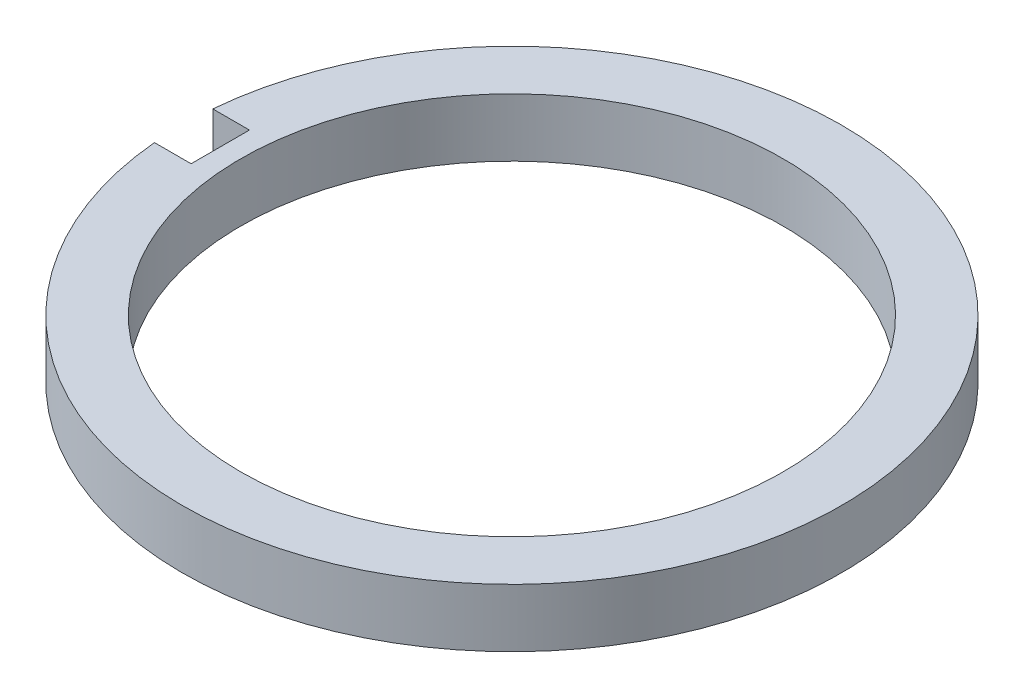
SolidWorks part; units mm, degrees
ref_plane "Front Plane" through (0, 0, 0) normal (0, 0, 1) x (1, 0, 0)
ref_plane "Top Plane" through (0, 0, 0) normal (0, 1, 0) x (1, 0, 0)
ref_plane "Right Plane" through (0, 0, 0) normal (1, 0, 0) x (0, 0, -1)
sketch "Sketch1" plane through (0, 0, 0) normal (0, 1, 0) x (1, 0, 0)
  circle A0 centre (0, 0) radius 59.055
  circle A1 centre (0, 0) radius 71.755
  dimension "D1" = 118.11
  dimension "D2" = 12.7
extrude "Boss-Extrude1" add sketch "Sketch1" along normal blind 12.7
sketch "Sketch2" plane through (0, 12.7, 0) normal (0, 1, 0) x (1, 0, 0)
  line L0 (0, 0) -> (-104.1472, 0) construction
  line L1 (-88.9, 6.35) -> (-63.5, 6.35)
  line L2 (-88.9, 6.35) -> (-88.9, -6.35)
  line L3 (-88.9, -6.35) -> (-63.5, -6.35)
  line L4 (-63.5, 6.35) -> (-63.5, -6.35)
  circle A0 centre (0, 0) radius 59.055 construction
  dimension "D1" = 12.7
  dimension "D2" = 63.5
  dimension "D3" = 25.4
extrude "Cut-Extrude1" cut sketch "Sketch2" against normal through all
